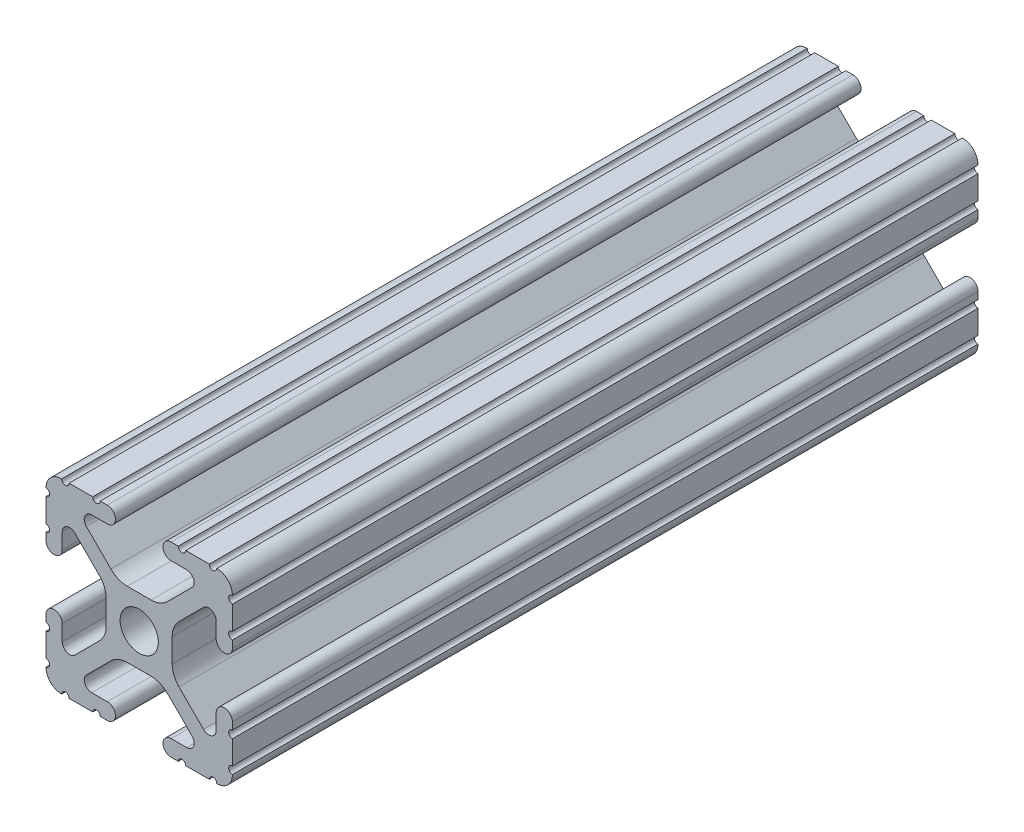
SolidWorks part; units mm, degrees
ref_plane "Front Plane" through (0, 0, 0) normal (0, 0, 1) x (1, 0, 0)
ref_plane "Top Plane" through (0, 0, 0) normal (0, 1, 0) x (1, 0, 0)
ref_plane "Right Plane" through (0, 0, 0) normal (1, 0, 0) x (0, 0, -1)
ref_plane "Plane1" through (0, 0, -2463.8) normal (0, 0, -1) x (-1, 0, 0)
sketch "Sketch1" plane through (0, 0, -2463.8) normal (0, 0, -1) x (-1, 0, 0)
  line L0 (12.7, -9.5504) -> (12.7, -6.3331)
  line L1 (12.7, -5.3171) -> (12.7, -4.3434)
  line L2 (10.4902, -4.3434) -> (10.4902, -6.4748)
  line L3 (8.7558, -7.1932) -> (5.4257, -3.8632)
  line L4 (4.4958, -1.6181) -> (4.4958, 1.6181)
  line L5 (5.4257, 3.8632) -> (8.7558, 7.1932)
  line L6 (10.4902, 6.4748) -> (10.4902, 4.3434)
  line L7 (12.7, 4.3434) -> (12.7, 5.3171)
  line L8 (12.7, 6.3331) -> (12.7, 9.5504)
  line L9 (9.5504, 12.7) -> (6.3331, 12.7)
  line L10 (5.3171, 12.7) -> (4.3434, 12.7)
  line L11 (4.3434, 10.4902) -> (6.4748, 10.4902)
  line L12 (7.1932, 8.7558) -> (3.8632, 5.4257)
  line L13 (1.6181, 4.4958) -> (-1.6181, 4.4958)
  line L14 (-3.8632, 5.4257) -> (-7.1932, 8.7558)
  line L15 (-6.4748, 10.4902) -> (-4.3434, 10.4902)
  line L16 (-4.3434, 12.7) -> (-5.3171, 12.7)
  line L17 (-6.3331, 12.7) -> (-9.5504, 12.7)
  line L18 (-12.7, 9.5504) -> (-12.7, 6.3331)
  line L19 (-12.7, 5.3171) -> (-12.7, 4.3434)
  line L20 (-10.4902, 4.3434) -> (-10.4902, 6.4748)
  line L21 (-8.7558, 7.1932) -> (-5.4257, 3.8632)
  line L22 (-4.4958, 1.6181) -> (-4.4958, -1.6181)
  line L23 (-5.4257, -3.8632) -> (-8.7558, -7.1932)
  line L24 (-10.4902, -6.4748) -> (-10.4902, -4.3434)
  line L25 (-12.7, -4.3434) -> (-12.7, -5.3171)
  line L26 (-12.7, -6.3331) -> (-12.7, -9.5504)
  line L27 (-9.5504, -12.7) -> (-6.3331, -12.7)
  line L28 (-5.3171, -12.7) -> (-4.3434, -12.7)
  line L29 (-4.3434, -10.4902) -> (-6.4748, -10.4902)
  line L30 (-7.1932, -8.7558) -> (-3.8632, -5.4257)
  line L31 (-1.6181, -4.4958) -> (1.6181, -4.4958)
  line L32 (3.8632, -5.4257) -> (7.1932, -8.7558)
  line L33 (6.4748, -10.4902) -> (4.3434, -10.4902)
  line L34 (4.3434, -12.7) -> (5.3171, -12.7)
  line L35 (6.3331, -12.7) -> (9.5504, -12.7)
  arc A0 (12.6998, -10.5664) -> (12.7, -9.5504) centre (12.7, -10.0584) cw
  arc A1 (12.7, -6.3331) -> (12.7, -5.3171) centre (12.7, -5.8251) cw
  arc A2 (12.7, -4.3434) -> (10.4902, -4.3434) centre (11.5951, -4.3434) ccw
  arc A3 (10.4902, -6.4748) -> (8.7558, -7.1932) centre (9.4742, -6.4748) cw
  arc A4 (5.4257, -3.8632) -> (4.4958, -1.6181) centre (7.6708, -1.6181) cw
  arc A5 (4.4958, 1.6181) -> (5.4257, 3.8632) centre (7.6708, 1.6181) cw
  arc A6 (8.7558, 7.1932) -> (10.4902, 6.4748) centre (9.4742, 6.4748) cw
  arc A7 (10.4902, 4.3434) -> (12.7, 4.3434) centre (11.5951, 4.3434) ccw
  arc A8 (12.7, 5.3171) -> (12.7, 6.3331) centre (12.7, 5.8251) cw
  arc A9 (12.7, 9.5504) -> (12.6998, 10.5664) centre (12.7, 10.0584) cw
  arc A10 (12.6998, 10.5664) -> (10.5664, 12.6998) centre (10.5918, 10.5918) ccw
  arc A11 (10.5664, 12.6998) -> (9.5504, 12.7) centre (10.0584, 12.7) cw
  arc A12 (6.3331, 12.7) -> (5.3171, 12.7) centre (5.8251, 12.7) cw
  arc A13 (4.3434, 12.7) -> (4.3434, 10.4902) centre (4.3434, 11.5951) ccw
  arc A14 (6.4748, 10.4902) -> (7.1932, 8.7558) centre (6.4748, 9.4742) cw
  arc A15 (3.8632, 5.4257) -> (1.6181, 4.4958) centre (1.6181, 7.6708) cw
  arc A16 (-1.6181, 4.4958) -> (-3.8632, 5.4257) centre (-1.6181, 7.6708) cw
  arc A17 (-7.1932, 8.7558) -> (-6.4748, 10.4902) centre (-6.4748, 9.4742) cw
  arc A18 (-4.3434, 10.4902) -> (-4.3434, 12.7) centre (-4.3434, 11.5951) ccw
  arc A19 (-5.3171, 12.7) -> (-6.3331, 12.7) centre (-5.8251, 12.7) cw
  arc A20 (-9.5504, 12.7) -> (-10.5664, 12.6998) centre (-10.0584, 12.7) cw
  arc A21 (-10.5664, 12.6998) -> (-12.6998, 10.5664) centre (-10.5918, 10.5918) ccw
  arc A22 (-12.6998, 10.5664) -> (-12.7, 9.5504) centre (-12.7, 10.0584) cw
  arc A23 (-12.7, 6.3331) -> (-12.7, 5.3171) centre (-12.7, 5.8251) cw
  arc A24 (-12.7, 4.3434) -> (-10.4902, 4.3434) centre (-11.5951, 4.3434) ccw
  arc A25 (-10.4902, 6.4748) -> (-8.7558, 7.1932) centre (-9.4742, 6.4748) cw
  arc A26 (-5.4257, 3.8632) -> (-4.4958, 1.6181) centre (-7.6708, 1.6181) cw
  arc A27 (-4.4958, -1.6181) -> (-5.4257, -3.8632) centre (-7.6708, -1.6181) cw
  arc A28 (-8.7558, -7.1932) -> (-10.4902, -6.4748) centre (-9.4742, -6.4748) cw
  arc A29 (-10.4902, -4.3434) -> (-12.7, -4.3434) centre (-11.5951, -4.3434) ccw
  arc A30 (-12.7, -5.3171) -> (-12.7, -6.3331) centre (-12.7, -5.8251) cw
  arc A31 (-12.7, -9.5504) -> (-12.6998, -10.5664) centre (-12.7, -10.0584) cw
  arc A32 (-12.6998, -10.5664) -> (-10.5664, -12.6998) centre (-10.5918, -10.5918) ccw
  arc A33 (-10.5664, -12.6998) -> (-9.5504, -12.7) centre (-10.0584, -12.7) cw
  arc A34 (-6.3331, -12.7) -> (-5.3171, -12.7) centre (-5.8251, -12.7) cw
  arc A35 (-4.3434, -12.7) -> (-4.3434, -10.4902) centre (-4.3434, -11.5951) ccw
  arc A36 (-6.4748, -10.4902) -> (-7.1932, -8.7558) centre (-6.4748, -9.4742) cw
  arc A37 (-3.8632, -5.4257) -> (-1.6181, -4.4958) centre (-1.6181, -7.6708) cw
  arc A38 (1.6181, -4.4958) -> (3.8632, -5.4257) centre (1.6181, -7.6708) cw
  arc A39 (7.1932, -8.7558) -> (6.4748, -10.4902) centre (6.4748, -9.4742) cw
  arc A40 (4.3434, -10.4902) -> (4.3434, -12.7) centre (4.3434, -11.5951) ccw
  arc A41 (5.3171, -12.7) -> (6.3331, -12.7) centre (5.8251, -12.7) cw
  arc A42 (9.5504, -12.7) -> (10.5664, -12.6998) centre (10.0584, -12.7) cw
  arc A43 (10.5664, -12.6998) -> (12.6998, -10.5664) centre (10.5918, -10.5918) ccw
  circle A44 centre (0, 0) radius 2.6035
extrude "Boss-Extrude1" add sketch "Sketch1" along normal blind 101.6
